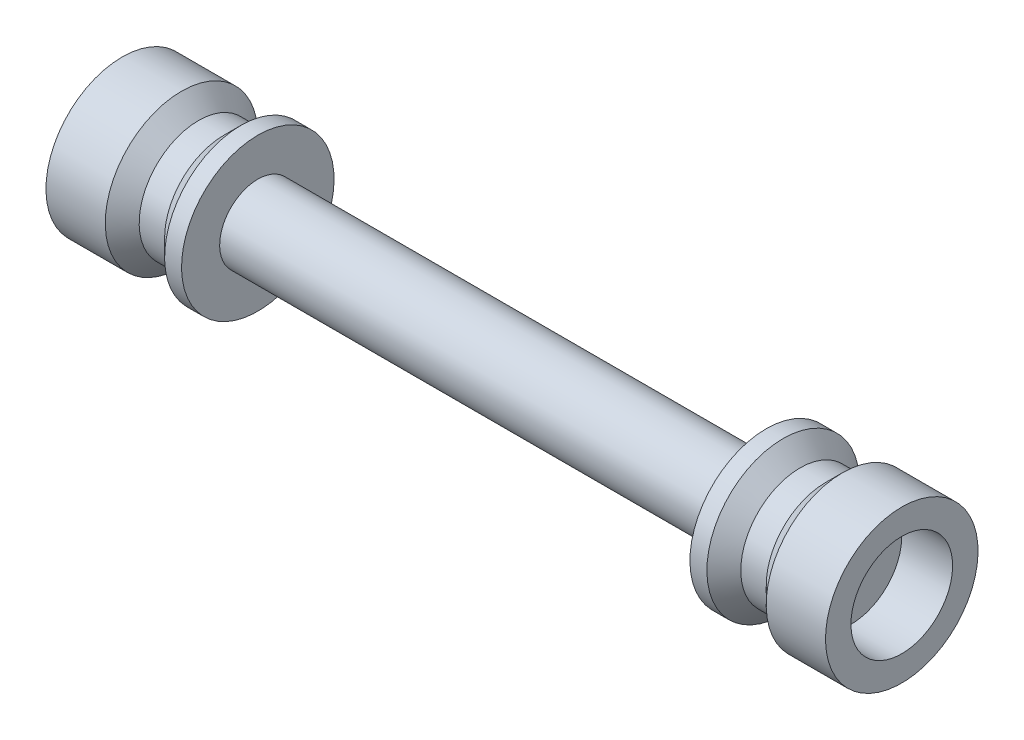
SolidWorks part; units mm, degrees
ref_plane "Front" through (0, 0, 0) normal (0, 0, 1) x (1, 0, 0)
ref_plane "Top" through (0, 0, 0) normal (0, 1, 0) x (1, 0, 0)
ref_plane "Right" through (0, 0, 0) normal (1, 0, 0) x (0, 0, -1)
sketch "Esquisse1" plane through (0, 0, 0) normal (0, 0, 1) x (1, 0, 0)
  line L0 (0, 0) -> (0, 11.3185) construction
  line L1 (0, 0) -> (-20, 0)
  line L2 (-20, 0) -> (-20, 3)
  line L3 (-20, 3) -> (-23, 3)
  line L4 (-23, 3) -> (-23, 4.5)
  line L5 (-23, 4.5) -> (-19.5, 4.5)
  line L6 (-19.5, 4.5) -> (-18.5, 3.5)
  line L7 (-18.5, 3.5) -> (-17, 3.5)
  line L8 (-17, 3.5) -> (-16, 4.5)
  line L9 (-16, 4.5) -> (-15, 4.5)
  line L10 (-15, 4.5) -> (-15, 2.25)
  line L11 (-15, 2.25) -> (15, 2.25)
  line L12 (15, 4.5) -> (15, 2.25)
  line L13 (16, 4.5) -> (15, 4.5)
  line L14 (17, 3.5) -> (16, 4.5)
  line L15 (18.5, 3.5) -> (17, 3.5)
  line L16 (19.5, 4.5) -> (18.5, 3.5)
  line L17 (23, 4.5) -> (19.5, 4.5)
  line L18 (23, 3) -> (23, 4.5)
  line L19 (20, 3) -> (23, 3)
  line L20 (20, 0) -> (20, 3)
  line L21 (0, 0) -> (20, 0)
  line L22 (0, 0) -> (-29.7186, 0) construction
  point P15 (0, 2.25)
  dimension "D1" = 30
  dimension "D2" = 4.5
  dimension "D3" = 9
  dimension "D4" = 7
  dimension "D5" = 45
  dimension "D6" = 8
  dimension "D7" = 1
  dimension "D8" = 1.5
  dimension "D9" = 1.5
  dimension "D10" = 3
revolve "Révolution1" add sketch "Esquisse1" angle 360 about L22
chamfer "Chanfrein1" [suppressed] distance 0.5 angle 45
